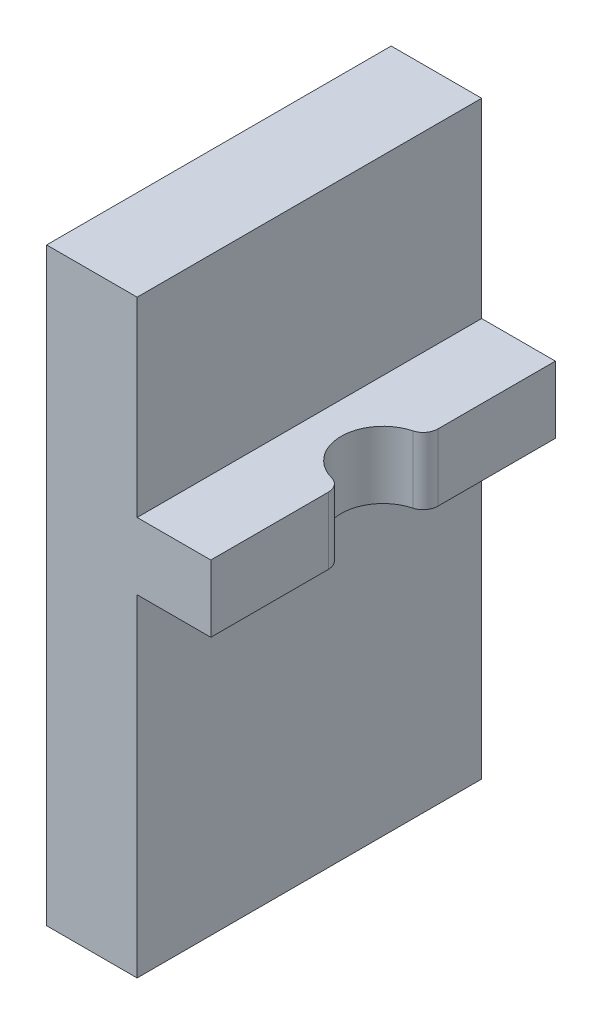
SolidWorks part; units mm, degrees
ref_plane "Front Plane" through (0, 0, 0) normal (0, 0, 1) x (1, 0, 0)
ref_plane "Top Plane" through (0, 0, 0) normal (0, 1, 0) x (1, 0, 0)
ref_plane "Right Plane" through (0, 0, 0) normal (1, 0, 0) x (0, 0, -1)
sketch "Sketch1" plane through (0, 0, 0) normal (0, 1, 0) x (1, 0, 0)
  line L1 (-34.9417, 19.5957) -> (-22.6649, 19.5957)
  line L2 (-34.9417, 19.5957) -> (-34.9417, -27.1506)
  line L3 (-34.9417, -27.1506) -> (-22.6649, -27.1506)
  line L4 (-22.6649, 19.5957) -> (-22.6649, -27.1506)
extrude "Boss-Extrude1" add sketch "Sketch1" along normal blind 80
sketch "Sketch8" plane through (-22.6649, 0, 0) normal (1, 0, 0) x (0, 0, -1)
  line L0 (-27.1506, 80) -> (-27.1506, 0) construction
  line L1 (-27.1506, 54.1142) -> (19.5957, 54.1142)
  line L2 (-27.1506, 54.1142) -> (-27.1506, 45.0345)
  line L3 (-27.1506, 45.0345) -> (19.5957, 45.0345)
  line L4 (19.5957, 54.1142) -> (19.5957, 45.0345)
  line L5 (19.5957, 80) -> (19.5957, 0) construction
extrude "Boss-Extrude2" add sketch "Sketch8" along normal blind 10
sketch "Sketch10" plane through (0, 54.1142, 0) normal (0, 1, 0) x (1, 0, 0)
  line L0 (-12.6649, 19.5957) -> (-12.6649, -27.1506) construction
  circle A0 centre (-12.6649, -3.7775) radius 5.7049
extrude "Cut-Extrude1" cut sketch "Sketch10" against normal up to next
fillet "Fillet1" radius 2 2 edges at (-12.6649, 49.5744, 9.4823) (-12.6649, 49.5744, -1.9274)
